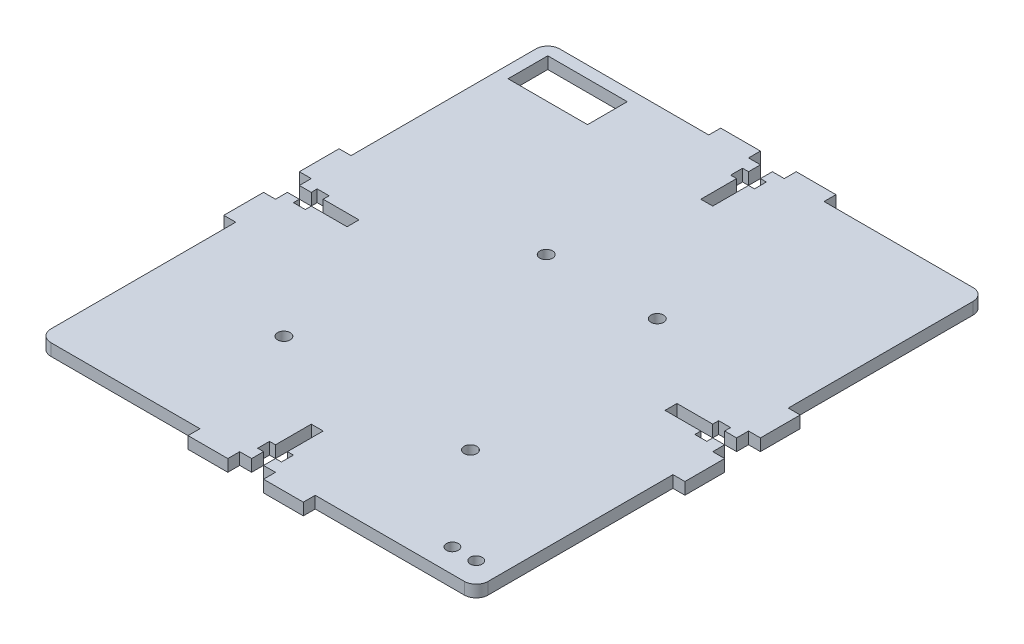
SolidWorks part; units mm, degrees
ref_plane "Front Plane" through (0, 0, 0) normal (0, 0, 1) x (1, 0, 0)
ref_plane "Top Plane" through (0, 0, 0) normal (0, 1, 0) x (1, 0, 0)
ref_plane "Right Plane" through (0, 0, 0) normal (1, 0, 0) x (0, 0, -1)
sketch "Sketch1" plane through (0, 0, 0) normal (0, 1, 0) x (1, 0, 0)
  line L0 (55, 128) -> (55, 0) construction
  line L1 (0, 0) -> (110, 0)
  line L2 (0, 0) -> (0, 128)
  line L3 (0, 128) -> (110, 128)
  line L4 (110, 0) -> (110, 128)
  line L5 (0, 64) -> (110, 64) construction
  line L6 (107, 67) -> (107, 61)
  line L7 (0, 65.5) -> (15, 65.5)
  line L8 (0, 65.5) -> (0, 62.5)
  line L9 (0, 62.5) -> (15, 62.5)
  line L10 (15, 65.5) -> (15, 62.5)
  line L11 (3, 67) -> (6, 67)
  line L12 (3, 67) -> (3, 61)
  line L13 (3, 61) -> (6, 61)
  line L14 (6, 67) -> (6, 61)
  line L15 (107, 61) -> (104, 61)
  line L16 (104, 67) -> (104, 61)
  line L17 (107, 67) -> (104, 67)
  line L18 (110, 65.5) -> (110, 62.5)
  line L19 (110, 62.5) -> (95, 62.5)
  line L20 (95, 65.5) -> (95, 62.5)
  line L21 (110, 65.5) -> (95, 65.5)
  line L22 (0, 59.5) -> (0, 49.5)
  line L23 (0, 68.5) -> (-3, 68.5)
  line L24 (0, 68.5) -> (0, 78.5)
  line L25 (0, 78.5) -> (-3, 78.5)
  line L26 (-3, 68.5) -> (-3, 78.5)
  line L27 (0, 59.5) -> (-3, 59.5)
  line L28 (-3, 59.5) -> (-3, 49.5)
  line L29 (0, 49.5) -> (-3, 49.5)
  line L30 (110, 59.5) -> (110, 49.5)
  line L31 (110, 49.5) -> (113, 49.5)
  line L32 (113, 59.5) -> (113, 49.5)
  line L33 (110, 59.5) -> (113, 59.5)
  line L34 (110, 68.5) -> (110, 78.5)
  line L35 (110, 68.5) -> (113, 68.5)
  line L36 (113, 68.5) -> (113, 78.5)
  line L37 (110, 78.5) -> (113, 78.5)
  line L38 (69.5, 128) -> (69.5, 131)
  line L39 (53.5, 128) -> (56.5, 128)
  line L40 (53.5, 128) -> (53.5, 113)
  line L41 (53.5, 113) -> (56.5, 113)
  line L42 (56.5, 128) -> (56.5, 113)
  line L43 (52, 125) -> (58, 125)
  line L44 (52, 125) -> (52, 122)
  line L45 (52, 122) -> (58, 122)
  line L46 (58, 125) -> (58, 122)
  line L47 (40.5, 128) -> (50.5, 128)
  line L48 (40.5, 128) -> (40.5, 131)
  line L49 (40.5, 131) -> (50.5, 131)
  line L50 (50.5, 128) -> (50.5, 131)
  line L51 (69.5, 128) -> (59.5, 128)
  line L52 (59.5, 128) -> (59.5, 131)
  line L53 (69.5, 131) -> (59.5, 131)
  line L54 (52, 3) -> (58, 3)
  line L55 (58, 3) -> (58, 6)
  line L56 (52, 6) -> (58, 6)
  line L57 (52, 3) -> (52, 6)
  line L58 (53.5, 0) -> (56.5, 0)
  line L59 (56.5, 0) -> (56.5, 15)
  line L60 (53.5, 15) -> (56.5, 15)
  line L61 (53.5, 0) -> (53.5, 15)
  line L62 (69.5, 0) -> (69.5, -3)
  line L63 (69.5, 0) -> (59.5, 0)
  line L64 (59.5, 0) -> (59.5, -3)
  line L65 (69.5, -3) -> (59.5, -3)
  line L66 (40.5, 0) -> (40.5, -3)
  line L67 (40.5, 0) -> (50.5, 0)
  line L68 (50.5, 0) -> (50.5, -3)
  line L69 (40.5, -3) -> (50.5, -3)
  point P13 (0, 64)
  point P18 (3, 64)
  point P55 (55, 113)
  point P56 (55, 125)
  dimension "D11" = 3
  dimension "D1" = 128
  dimension "D2" = 110
  dimension "D3" = 3
  dimension "D4" = 3
  dimension "D5" = 6
  dimension "D6" = 3
  dimension "D7" = 15
  dimension "D8" = 10
  dimension "D9" = 4.5
  dimension "D10" = 3
  dimension "D12" = 6
  dimension "D13" = 3
  dimension "D14" = 15
  dimension "D15" = 10
  dimension "D16" = 3
  dimension "D17" = 4.5
  dimension "D18" = 3
extrude "Boss-Extrude2" add sketch "Sketch1" along normal blind 3
fillet "Fillet1" radius 3 4 edges at (0, 1.5, 0) (0, 1.5, -128) (110, 1.5, -128) (110, 1.5, 0)
sketch "Sketch2" plane through (0, 3, 0) normal (0, 1, 0) x (1, 0, 0)
  line L0 (79.15, 9.4) -> (79.15, 78) construction
  line L1 (28.35, 9.4) -> (28.35, 78) construction
  line L2 (28.35, 9.4) -> (81.65, 9.4) construction
  line L3 (81.65, 9.4) -> (81.65, 78) construction
  line L4 (28.35, 78) -> (81.65, 78) construction
  line L5 (55, 128) -> (55, 15) construction
  line L6 (3, 128) -> (40.5, 128) construction
  line L8 (53.5, 15) -> (56.5, 15) construction
  line L9 (81.65, 29.4) -> (28.35, 29.4) construction
  line L10 (81.65, 81.5) -> (28.35, 81.5) construction
  line L11 (30.91, 9.4) -> (30.91, 78) construction
  circle A0 centre (74.05, 81.5) radius 1.6
  circle A1 centre (46.11, 81.5) radius 1.6
  circle A2 centre (79.15, 29.4) radius 1.6
  circle A3 centre (30.91, 30.7) radius 1.6
  point P26 (55, 78)
  dimension "D3" = 3.2
  dimension "D4" = 2.5
  dimension "D6" = 3.2
  dimension "D8" = 3.2
  dimension "D9" = 3.2
  dimension "D1" = 53.3
  dimension "D2" = 68.6
  dimension "D5" = 5.1
  dimension "D7" = 27.94
  dimension "D10" = 20
  dimension "D11" = 1.3
  dimension "D12" = 50.8
  dimension "D13" = 15.2
  dimension "D14" = 50
extrude "Cut-Extrude1" cut sketch "Sketch2" against normal blind 3
sketch "Sketch3" plane through (0, 3, 0) normal (0, 1, 0) x (1, 0, 0)
  line L0 (98, 6) -> (104, 6) construction
  line L1 (110, 3) -> (110, 49.5) construction
  line L2 (3, 0) -> (40.5, 0) construction
  circle A0 centre (98, 6) radius 1.5
  circle A1 centre (104, 6) radius 1.5
  dimension "D1" = 3
  dimension "D2" = 6
  dimension "D3" = 6
  dimension "D4" = 6
extrude "Cut-Extrude2" cut sketch "Sketch3" against normal blind 10
sketch "Sketch4" plane through (0, 3, 0) normal (0, 1, 0) x (1, 0, 0)
  line L0 (15, 64) -> (95, 64) construction
  line L1 (3, 125) -> (23, 125)
  line L2 (3, 125) -> (3, 115)
  line L3 (3, 115) -> (23, 115)
  line L4 (23, 125) -> (23, 115)
  line L5 (15, 65.5) -> (15, 62.5) construction
  line L6 (95, 65.5) -> (95, 62.5) construction
  line L7 (21.75, 128) -> (21.75, 0) construction
  line L8 (3, 128) -> (40.5, 128) construction
  line L9 (3, 0) -> (40.5, 0) construction
  line L10 (0, 78.5) -> (0, 125) construction
  dimension "D1" = 20
  dimension "D2" = 10
  dimension "D3" = 3
  dimension "D4" = 3
extrude "Cut-Extrude3" cut sketch "Sketch4" against normal blind 10
